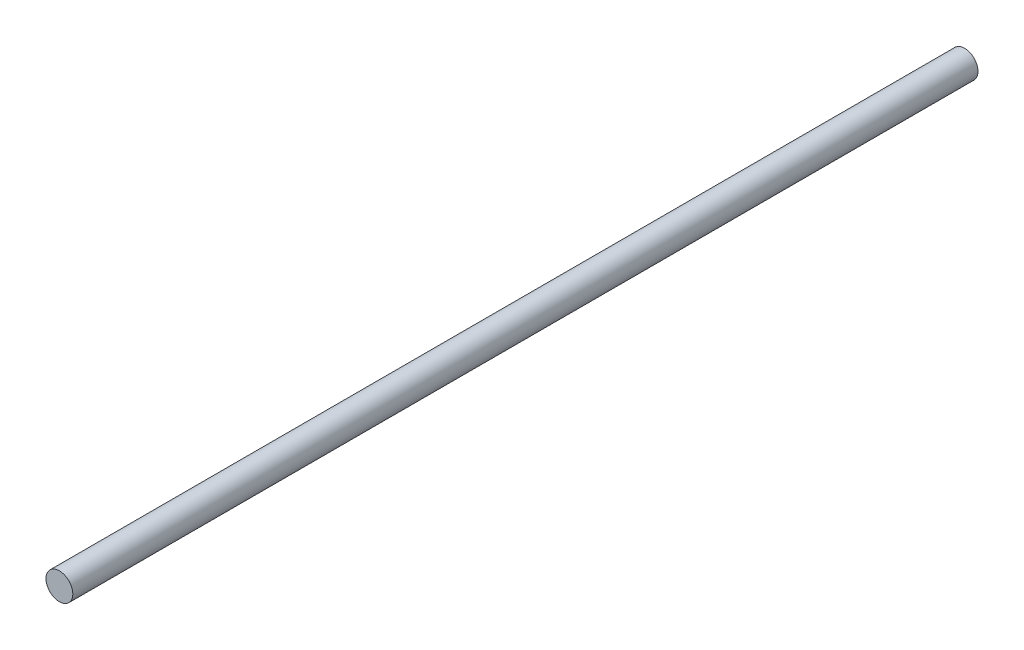
SolidWorks part; units mm, degrees
material "AISI 1045 Steel, cold drawn"
ref_plane "Front Plane" through (0, 0, 0) normal (0, 0, 1) x (1, 0, 0)
ref_plane "Top Plane" through (0, 0, 0) normal (0, 1, 0) x (1, 0, 0)
ref_plane "Right Plane" through (0, 0, 0) normal (1, 0, 0) x (0, 0, -1)
sketch "Sketch1" plane through (0, 0, 0) normal (0, 0, 1) x (1, 0, 0)
  circle A0 centre (0, 0) radius 6
  dimension "D1" = 12
extrude "Boss-Extrude1" add sketch "Sketch1" along normal blind 405
